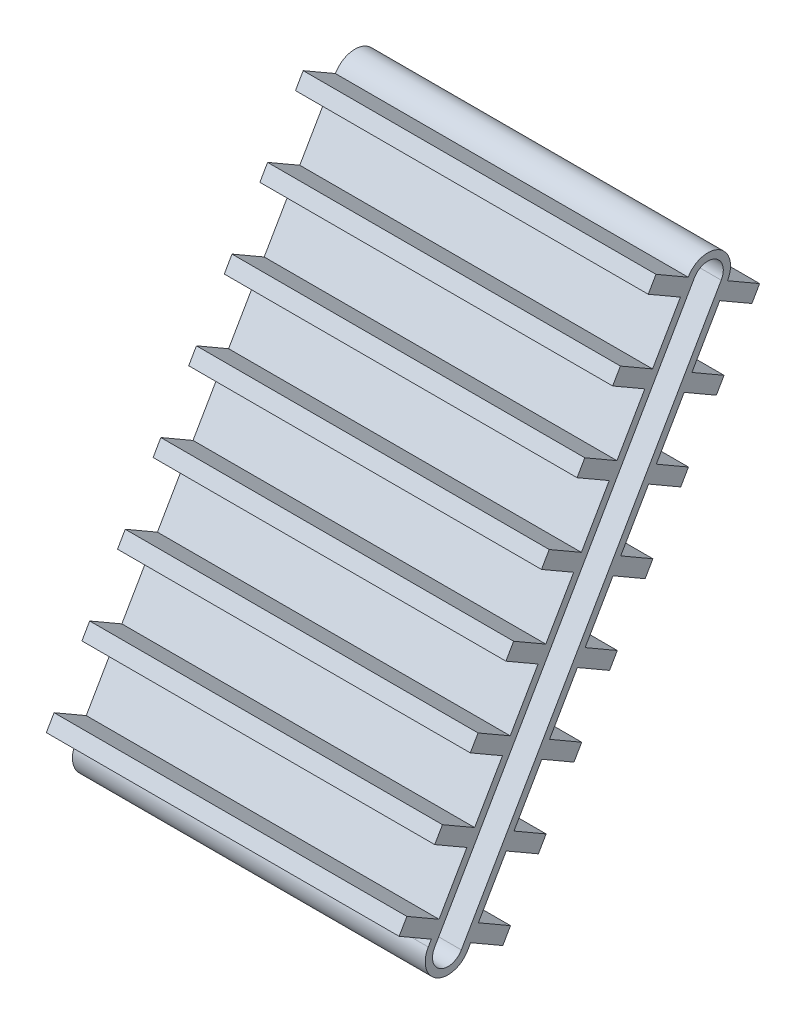
SolidWorks part; units mm, degrees
ref_plane "Front Plane" through (0, 0, 0) normal (0, 0, 1) x (1, 0, 0)
ref_plane "Top Plane" through (0, 0, 0) normal (0, 1, 0) x (1, 0, 0)
ref_plane "Right Plane" through (0, 0, 0) normal (1, 0, 0) x (0, 0, -1)
sketch "Sketch1" plane through (0, 0, 0) normal (1, 0, 0) x (0, 0, -1)
  line L0 (0, 0) -> (0, -1926.3)
  line L1 (0, 0) -> (-1112.1498, -1926.3) construction
  line L2 (0, -1926.3) -> (-1112.1498, -1926.3) construction
  line L10 (-1112.1498, -1926.3) -> (-2683.325, -1926.3) construction
  line L13 (-938.9447, -1626.3) -> (-1499.6035, -2096.7486)
  line L14 (-938.9447, -1626.3) -> (-1003.2235, -1549.6956)
  line L15 (-1003.2235, -1549.6956) -> (-1452.0432, -1926.3)
  line L16 (-1499.6035, -2096.7486) -> (-1534.8215, -2126.3)
  line L17 (-776.1785, -1491.1806) -> (-929.8086, -1757.2758)
  line L18 (-903.311, -1417.7806) -> (-63.5663, 36.7)
  line L19 (-903.311, -1417.7806) -> (-839.7447, -1454.4806) construction
  line L20 (-883.046, -1429.4806) -> (-43.3013, 25)
  line L21 (-776.1785, -1491.1806) -> (63.5663, -36.7)
  line L22 (-796.4435, -1479.4806) -> (43.3013, -25)
  line L24 (-1296.4708, -1926.3) -> (-1296.4708, -2126.3) construction
  line L25 (-1296.4708, -2126.3) -> (-1534.8215, -2126.3) construction
  line L26 (-1452.0432, -1926.3) -> (-1534.8215, -2126.3)
  line L27 (-929.8086, -1757.2758) -> (-1143.5437, -1633.8758)
  line L28 (-1143.5437, -1633.8758) -> (-81.6121, 205.4437)
  line L29 (63.5663, -36.7) -> (132.123, 82.0437)
  line L30 (132.123, 82.0437) -> (-81.6121, 205.4437)
  line L31 (0, 55) -> (0, -55) construction
  line L32 (55, 0) -> (-55, 0) construction
  arc A0 (-883.046, -1429.4806) -> (-796.4435, -1479.4806) centre (-839.7447, -1454.4806) ccw
  arc A1 (43.3013, -25) -> (-43.3013, 25) centre (0, 0) ccw
  arc A2 (-903.311, -1417.7806) -> (-776.1785, -1491.1806) centre (-839.7447, -1454.4806) ccw
  arc A5 (63.5663, -36.7) -> (-63.5663, 36.7) centre (0, 0) ccw
  dimension "D6" = 100
  dimension "D7" = 146.8
  dimension "D8" = 200
  dimension "D1" = 1926.3
  dimension "D2" = 300
  dimension "D3" = 100
  dimension "D4" = 198.4
  dimension "D5" = 60
  dimension "D9" = 100
extrude "Boss-Extrude1" add sketch "Sketch1" along normal blind 1140
sketch "Sketch2" plane through (0, 36.7, 63.5663) normal (0, 0.5, 0.866) x (1, 0, 0)
  line L0 (1140, -1679.4895) -> (1140, 0) construction
  line L1 (0, 0) -> (1140, 0)
  line L2 (0, 0) -> (0, -50)
  line L3 (0, -50) -> (1140, -50)
  line L4 (1140, 0) -> (1140, -50)
  dimension "D1" = 50
extrude "Boss-Extrude2" add sketch "Sketch2" along normal blind 120
pattern_linear "LPattern1" count 8 spacing 230 along (0, -0.866, 0.5) of "Boss-Extrude2"
sketch "Sketch3" plane through (0, -36.7, -63.5663) normal (0, -0.5, -0.866) x (-1, 0, 0)
  line L0 (0, -1679.4895) -> (0, 0) construction
  line L1 (-1140, 0) -> (0, 0)
  line L2 (-1140, 0) -> (-1140, -50)
  line L3 (-1140, -50) -> (0, -50)
  line L4 (0, 0) -> (0, -50)
  dimension "D1" = 50
extrude "Boss-Extrude3" add sketch "Sketch3" along normal blind 120
pattern_linear "LPattern2" count 8 spacing 230 along (0, -0.866, 0.5) of "Boss-Extrude3"
